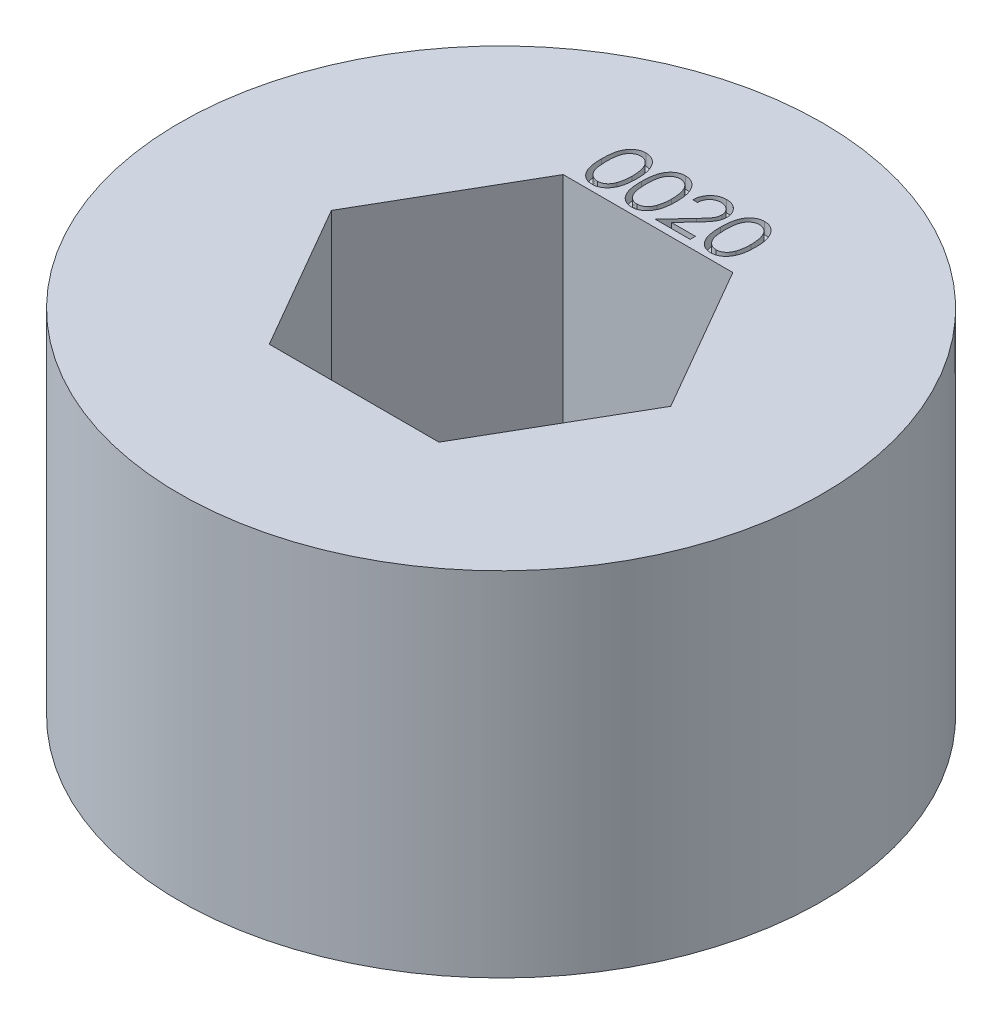
SolidWorks part; units mm, degrees
material "Nylon 101"
ref_plane "Front Plane" through (0, 0, 0) normal (0, 0, 1) x (1, 0, 0)
ref_plane "Top Plane" through (0, 0, 0) normal (0, 1, 0) x (1, 0, 0)
ref_plane "Right Plane" through (0, 0, 0) normal (1, 0, 0) x (0, 0, -1)
sketch "Sketch1" plane through (0, 0, 0) normal (0, 1, 0) x (1, 0, 0)
  line L1 (-2.9329, 5.08) -> (-5.8659, 0)
  line L2 (-5.8659, 0) -> (-2.9329, -5.08)
  line L3 (-2.9329, -5.08) -> (2.9329, -5.08)
  line L4 (2.9329, -5.08) -> (5.8659, 0)
  line L5 (5.8659, 0) -> (2.9329, 5.08)
  line L6 (2.9329, 5.08) -> (-2.9329, 5.08)
  circle A0 centre (0, 0) radius 11.1125
  circle A1 centre (0, 0) radius 5.08 construction
  dimension "D1" = 22.225
  dimension "D2" = 10.16
extrude "Boss-Extrude1" add sketch "Sketch1" along normal blind 12.192
sketch "Sketch2" plane through (0, 12.192, 0) normal (0, 1, 0) x (1, 0, 0)
  line L0 (-2.81, 5.334) -> (2.8909, 5.334) construction
  line L1 (2.9329, 5.08) -> (-2.9329, 5.08) construction
  text T0 "0020" font "Century Gothic" height 1.778
  dimension "D1" = 0.254
extrude "Cut-Extrude1" cut sketch "Sketch2" against normal blind 0.4
